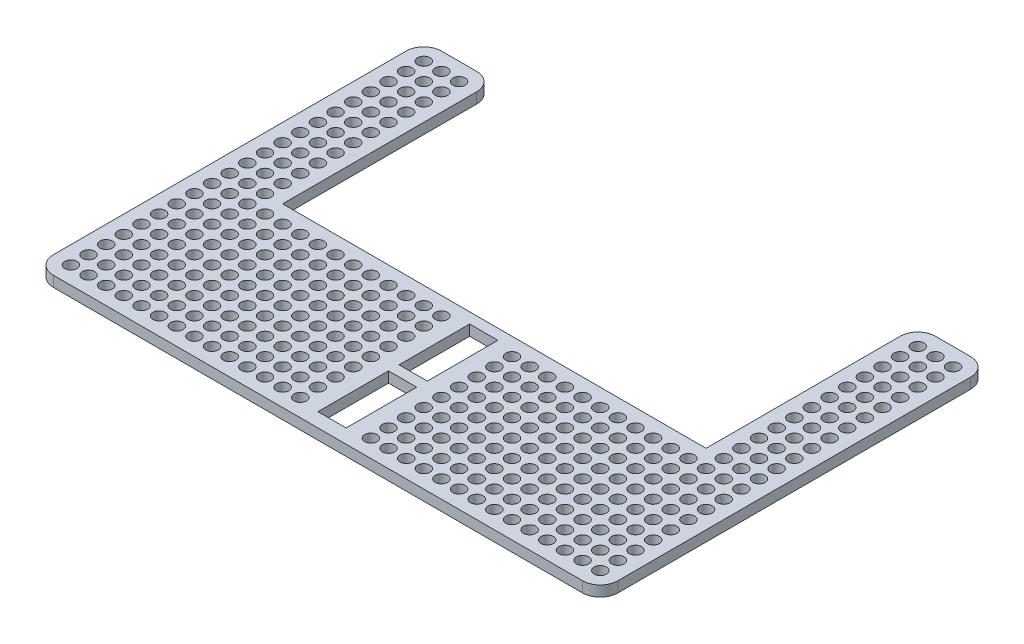
SolidWorks part; units mm, degrees
ref_plane "Front Plane" through (0, 0, 0) normal (0, 0, 1) x (1, 0, 0)
ref_plane "Top Plane" through (0, 0, 0) normal (0, 1, 0) x (1, 0, 0)
ref_plane "Right Plane" through (0, 0, 0) normal (1, 0, 0) x (0, 0, -1)
sketch "Sketch1" plane through (0, 0, 0) normal (0, 1, 0) x (1, 0, 0)
  line L0 (0, 0) -> (-65, 0) construction
  line L1 (0, 0) -> (0, 43.8925) construction
  line L2 (0, -20) -> (-60, -20)
  line L3 (-60, -20) -> (-60, 35)
  line L4 (-65, 40) -> (-75, 40)
  line L5 (-80, 35) -> (-80, -65)
  line L6 (-75, -70) -> (0, -70)
  line L7 (0, -70) -> (0, -66)
  line L8 (0, -23) -> (0, -20)
  line L9 (0, -23) -> (-4, -23)
  line L11 (0, -43) -> (-4, -43)
  line L12 (-4, -23) -> (-4, -43)
  line L13 (0, -46) -> (-4, -46)
  line L15 (0, -66) -> (-4, -66)
  line L16 (-4, -46) -> (-4, -66)
  line L17 (0, -46) -> (0, -43)
  circle A0 centre (-65, 0) radius 1.75
  circle A32 centre (-70, 0) radius 1.75
  circle A33 centre (-75, 0) radius 1.75
  circle A34 centre (-75, 5) radius 1.75
  circle A35 centre (-70, 5) radius 1.75
  circle A36 centre (-65, 5) radius 1.75
  circle A37 centre (-75, 10) radius 1.75
  circle A38 centre (-70, 10) radius 1.75
  circle A39 centre (-65, 10) radius 1.75
  circle A40 centre (-75, 15) radius 1.75
  circle A41 centre (-70, 15) radius 1.75
  circle A42 centre (-65, 15) radius 1.75
  circle A43 centre (-75, 20) radius 1.75
  circle A44 centre (-70, 20) radius 1.75
  circle A45 centre (-65, 20) radius 1.75
  circle A46 centre (-75, 25) radius 1.75
  circle A47 centre (-70, 25) radius 1.75
  circle A48 centre (-65, 25) radius 1.75
  circle A49 centre (-75, 30) radius 1.75
  circle A50 centre (-70, 30) radius 1.75
  circle A51 centre (-65, 30) radius 1.75
  arc A52 (-80, -65) -> (-75, -70) centre (-75, -65) ccw
  arc A53 (-60, 35) -> (-65, 40) centre (-65, 35) ccw
  arc A54 (-75, 40) -> (-80, 35) centre (-75, 35) ccw
  circle A55 centre (-75, 35) radius 1.75
  circle A56 centre (-70, 35) radius 1.75
  circle A57 centre (-65, 35) radius 1.75
  circle A58 centre (-75, -5) radius 1.75
  circle A59 centre (-70, -5) radius 1.75
  circle A60 centre (-65, -5) radius 1.75
  circle A61 centre (-75, -10) radius 1.75
  circle A62 centre (-70, -10) radius 1.75
  circle A63 centre (-65, -10) radius 1.75
  circle A64 centre (-75, -15) radius 1.75
  circle A65 centre (-70, -15) radius 1.75
  circle A66 centre (-65, -15) radius 1.75
  circle A67 centre (-75, -20) radius 1.75
  circle A68 centre (-70, -20) radius 1.75
  circle A69 centre (-65, -20) radius 1.75
  circle A70 centre (-75, -25) radius 1.75
  circle A71 centre (-70, -25) radius 1.75
  circle A72 centre (-65, -25) radius 1.75
  circle A73 centre (-75, -30) radius 1.75
  circle A74 centre (-70, -30) radius 1.75
  circle A75 centre (-65, -30) radius 1.75
  circle A76 centre (-75, -35) radius 1.75
  circle A77 centre (-70, -35) radius 1.75
  circle A78 centre (-65, -35) radius 1.75
  circle A79 centre (-75, -40) radius 1.75
  circle A80 centre (-70, -40) radius 1.75
  circle A81 centre (-65, -40) radius 1.75
  circle A82 centre (-75, -45) radius 1.75
  circle A83 centre (-70, -45) radius 1.75
  circle A84 centre (-65, -45) radius 1.75
  circle A85 centre (-75, -50) radius 1.75
  circle A86 centre (-70, -50) radius 1.75
  circle A87 centre (-65, -50) radius 1.75
  circle A88 centre (-75, -55) radius 1.75
  circle A89 centre (-70, -55) radius 1.75
  circle A90 centre (-65, -55) radius 1.75
  circle A91 centre (-75, -60) radius 1.75
  circle A92 centre (-70, -60) radius 1.75
  circle A93 centre (-65, -60) radius 1.75
  circle A94 centre (-75, -65) radius 1.75
  circle A95 centre (-70, -65) radius 1.75
  circle A96 centre (-65, -65) radius 1.75
  circle A97 centre (-60, -65) radius 1.75
  circle A98 centre (-60, -60) radius 1.75
  circle A99 centre (-60, -55) radius 1.75
  circle A100 centre (-60, -50) radius 1.75
  circle A101 centre (-60, -45) radius 1.75
  circle A102 centre (-60, -40) radius 1.75
  circle A103 centre (-60, -35) radius 1.75
  circle A104 centre (-60, -30) radius 1.75
  circle A105 centre (-60, -25) radius 1.75
  circle A106 centre (-55, -65) radius 1.75
  circle A107 centre (-55, -60) radius 1.75
  circle A108 centre (-55, -55) radius 1.75
  circle A109 centre (-55, -50) radius 1.75
  circle A110 centre (-55, -45) radius 1.75
  circle A111 centre (-55, -40) radius 1.75
  circle A112 centre (-55, -35) radius 1.75
  circle A113 centre (-55, -30) radius 1.75
  circle A114 centre (-55, -25) radius 1.75
  circle A115 centre (-50, -65) radius 1.75
  circle A116 centre (-50, -60) radius 1.75
  circle A117 centre (-50, -55) radius 1.75
  circle A118 centre (-50, -50) radius 1.75
  circle A119 centre (-50, -45) radius 1.75
  circle A120 centre (-50, -40) radius 1.75
  circle A121 centre (-50, -35) radius 1.75
  circle A122 centre (-50, -30) radius 1.75
  circle A123 centre (-50, -25) radius 1.75
  circle A124 centre (-45, -65) radius 1.75
  circle A125 centre (-45, -60) radius 1.75
  circle A126 centre (-45, -55) radius 1.75
  circle A127 centre (-45, -50) radius 1.75
  circle A128 centre (-45, -45) radius 1.75
  circle A129 centre (-45, -40) radius 1.75
  circle A130 centre (-45, -35) radius 1.75
  circle A131 centre (-45, -30) radius 1.75
  circle A132 centre (-45, -25) radius 1.75
  circle A133 centre (-40, -65) radius 1.75
  circle A134 centre (-40, -60) radius 1.75
  circle A135 centre (-40, -55) radius 1.75
  circle A136 centre (-40, -50) radius 1.75
  circle A137 centre (-40, -45) radius 1.75
  circle A138 centre (-40, -40) radius 1.75
  circle A139 centre (-40, -35) radius 1.75
  circle A140 centre (-40, -30) radius 1.75
  circle A141 centre (-40, -25) radius 1.75
  circle A142 centre (-35, -65) radius 1.75
  circle A143 centre (-35, -60) radius 1.75
  circle A144 centre (-35, -55) radius 1.75
  circle A145 centre (-35, -50) radius 1.75
  circle A146 centre (-35, -45) radius 1.75
  circle A147 centre (-35, -40) radius 1.75
  circle A148 centre (-35, -35) radius 1.75
  circle A149 centre (-35, -30) radius 1.75
  circle A150 centre (-35, -25) radius 1.75
  circle A151 centre (-30, -65) radius 1.75
  circle A152 centre (-30, -60) radius 1.75
  circle A153 centre (-30, -55) radius 1.75
  circle A154 centre (-30, -50) radius 1.75
  circle A155 centre (-30, -45) radius 1.75
  circle A156 centre (-30, -40) radius 1.75
  circle A157 centre (-30, -35) radius 1.75
  circle A158 centre (-30, -30) radius 1.75
  circle A159 centre (-30, -25) radius 1.75
  circle A160 centre (-25, -65) radius 1.75
  circle A161 centre (-25, -60) radius 1.75
  circle A162 centre (-25, -55) radius 1.75
  circle A163 centre (-25, -50) radius 1.75
  circle A164 centre (-25, -45) radius 1.75
  circle A165 centre (-25, -40) radius 1.75
  circle A166 centre (-25, -35) radius 1.75
  circle A167 centre (-25, -30) radius 1.75
  circle A168 centre (-25, -25) radius 1.75
  circle A169 centre (-20, -65) radius 1.75
  circle A170 centre (-20, -60) radius 1.75
  circle A171 centre (-20, -55) radius 1.75
  circle A172 centre (-20, -50) radius 1.75
  circle A173 centre (-20, -45) radius 1.75
  circle A174 centre (-20, -40) radius 1.75
  circle A175 centre (-20, -35) radius 1.75
  circle A176 centre (-20, -30) radius 1.75
  circle A177 centre (-20, -25) radius 1.75
  circle A178 centre (-15, -65) radius 1.75
  circle A179 centre (-15, -60) radius 1.75
  circle A180 centre (-15, -55) radius 1.75
  circle A181 centre (-15, -50) radius 1.75
  circle A182 centre (-15, -45) radius 1.75
  circle A183 centre (-15, -40) radius 1.75
  circle A184 centre (-15, -35) radius 1.75
  circle A185 centre (-15, -30) radius 1.75
  circle A186 centre (-15, -25) radius 1.75
  circle A187 centre (-10, -65) radius 1.75
  circle A188 centre (-10, -60) radius 1.75
  circle A189 centre (-10, -55) radius 1.75
  circle A190 centre (-10, -50) radius 1.75
  circle A191 centre (-10, -45) radius 1.75
  circle A192 centre (-10, -40) radius 1.75
  circle A193 centre (-10, -35) radius 1.75
  circle A194 centre (-10, -30) radius 1.75
  circle A195 centre (-10, -25) radius 1.75
  point P58 (-60, 40)
  dimension "D2" = 3.5
  dimension "D12" = 5
  dimension "D14" = 5
  dimension "D22" = 5
  dimension "D24" = 5
  dimension "D1" = 65
  dimension "D5" = 20
  dimension "D6" = 10
  dimension "D7" = 5
  dimension "D8" = 5
  dimension "D9" = 50
  dimension "D10" = 5
  dimension "D11" = 5
  dimension "D15" = 20
  dimension "D16" = 3
  dimension "D17" = 20
  dimension "D18" = 3
  dimension "D19" = 4
  dimension "D20" = 4
  dimension "D3" = 3
  dimension "D4" = 7
  dimension "D13" = 2
  dimension "D21" = 14
  dimension "D23" = 12
extrude "Boss-Extrude1" add sketch "Sketch1" along normal blind 3
ref_plane "Plane1" through (0, 0, 0) normal (1, 0, 0) x (0, 0, -1)
mirror "Mirror1" about plane through (0, 0, 0) normal (1, 0, 0) of "Boss-Extrude1"
